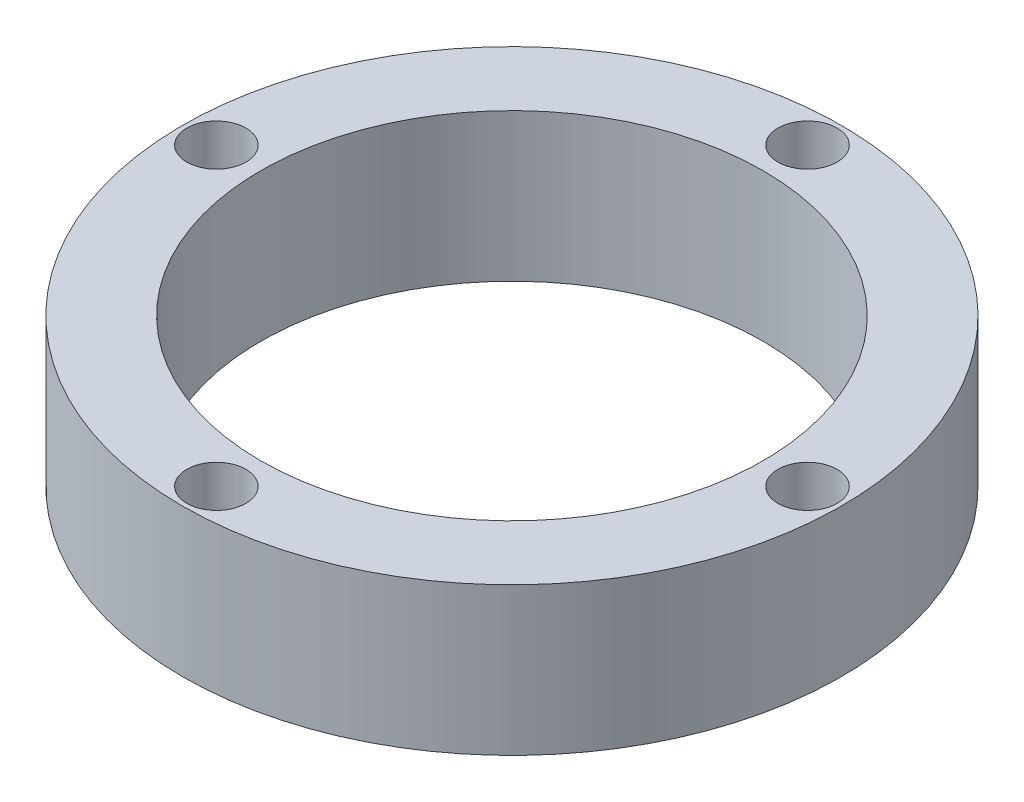
SolidWorks part; units mm, degrees
ref_plane "Front" through (0, 0, 0) normal (0, 0, 1) x (1, 0, 0)
ref_plane "Top" through (0, 0, 0) normal (0, 1, 0) x (1, 0, 0)
ref_plane "Right" through (0, 0, 0) normal (1, 0, 0) x (0, 0, -1)
sketch "Sketch1" plane through (0, 0, 0) normal (0, 1, 0) x (1, 0, 0)
  circle A0 centre (0, 0) radius 17
  circle A1 centre (0, 0) radius 22.3005
extrude "Boss-Extrude1" add sketch "Sketch1" along normal blind 10
sketch "Sketch2" plane through (0, 10, 0) normal (0, 1, 0) x (1, 0, 0)
  line L0 (0, 0) -> (0, 20)
  circle A0 centre (0, 20) radius 2
  circle A1 centre (20, 0) radius 2
  circle A2 centre (0, -20) radius 2
  circle A3 centre (-20, 0) radius 2
  point P13 (0, 0)
  dimension "D2" = 4
  dimension "D1" = 20
extrude "Cut-Extrude1" cut sketch "Sketch2" against normal through all
